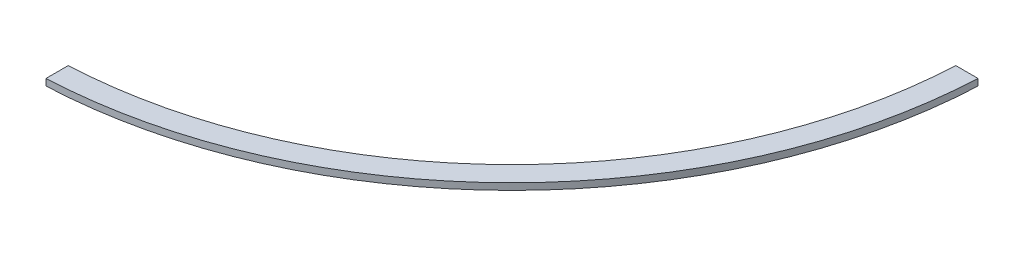
SolidWorks part; units mm, degrees
ref_plane "Front Plane" through (0, 0, 0) normal (0, 0, 1) x (1, 0, 0)
ref_plane "Top Plane" through (0, 0, 0) normal (0, 1, 0) x (1, 0, 0)
ref_plane "Right Plane" through (0, 0, 0) normal (1, 0, 0) x (0, 0, -1)
sketch "Sketch1" plane through (0, 0, 0) normal (0, 1, 0) x (1, 0, 0)
  circle A0 centre (0, 0) radius 210
  circle A1 centre (0, 0) radius 220
  dimension "D1" = 420
  dimension "D2" = 440
extrude "Boss-Extrude1" add sketch "Sketch1" along normal mid plane 3
sketch "pitch" plane through (0, 0, 0) normal (0, 1, 0) x (1, 0, 0)
  line L0 (-215, 0) -> (215, 0) construction
  dimension "D1" = 430
sketch "circle" plane through (0, 0, 0) normal (0, 1, 0) x (1, 0, 0)
  circle A0 centre (0, 0) radius 215 construction
sketch "Sketch2" plane through (0, 0, 0) normal (0, 1, 0) x (1, 0, 0)
  line L0 (-215, 0) -> (215, 0) construction
  line L1 (10, 220) -> (-10, 220)
  line L2 (10, 220) -> (10, -220)
  line L3 (10, -220) -> (-10, -220)
  line L4 (-10, 220) -> (-10, -220)
  line L5 (10, 220) -> (-10, -220) construction
  line L6 (10, -220) -> (-10, 220) construction
  line L8 (220, 10) -> (-220, 10)
  line L9 (220, 10) -> (220, -10)
  line L10 (220, -10) -> (-220, -10)
  line L11 (-220, 10) -> (-220, -10)
  line L12 (220, 10) -> (-220, -10) construction
  line L13 (220, -10) -> (-220, 10) construction
  circle A0 centre (0, 0) radius 220 construction
  point P0 (0, 0)
  point P10 (0, 0)
  dimension "D1" = 20
  dimension "D2" = 20
extrude "quadruple" cut sketch "Sketch2" against normal through all both and the other way through all contours L8 L11 L10 L9 | L4 L3 L2 L1
sketch "Sketch3" plane through (0, 0, 0) normal (0, 1, 0) x (1, 0, 0)
  line L0 (0, 220) -> (0, -220) construction
  circle A0 centre (0, 0) radius 220 construction
  circle A1 centre (0, 0) radius 220
sketch "Sketch4" plane through (0, 0, 0) normal (0, 0, 1) x (1, 0, 0)
  line L1 (219.7726, 1.5) -> (-219.7726, 1.5)
  line L2 (219.7726, 1.5) -> (219.7726, -1.5)
  line L3 (219.7726, -1.5) -> (-219.7726, -1.5)
  line L4 (-219.7726, 1.5) -> (-219.7726, -1.5)
  line L5 (219.7726, 1.5) -> (-219.7726, -1.5) construction
  line L6 (219.7726, -1.5) -> (-219.7726, 1.5) construction
  point P0 (0, 0)
  point P6 (0, 0)
extrude "half" cut sketch "Sketch4" against normal through all
sketch "Sketch5" plane through (0, 0, 0) normal (1, 0, 0) x (0, 0, -1)
  line L1 (219.7726, 1.5) -> (-219.7726, 1.5)
  line L2 (219.7726, 1.5) -> (219.7726, -1.5)
  line L3 (219.7726, -1.5) -> (-219.7726, -1.5)
  line L4 (-219.7726, 1.5) -> (-219.7726, -1.5)
  line L5 (219.7726, 1.5) -> (-219.7726, -1.5) construction
  line L6 (219.7726, -1.5) -> (-219.7726, 1.5) construction
  point P0 (0, 0)
extrude "quarter" cut sketch "Sketch5" against normal through all
